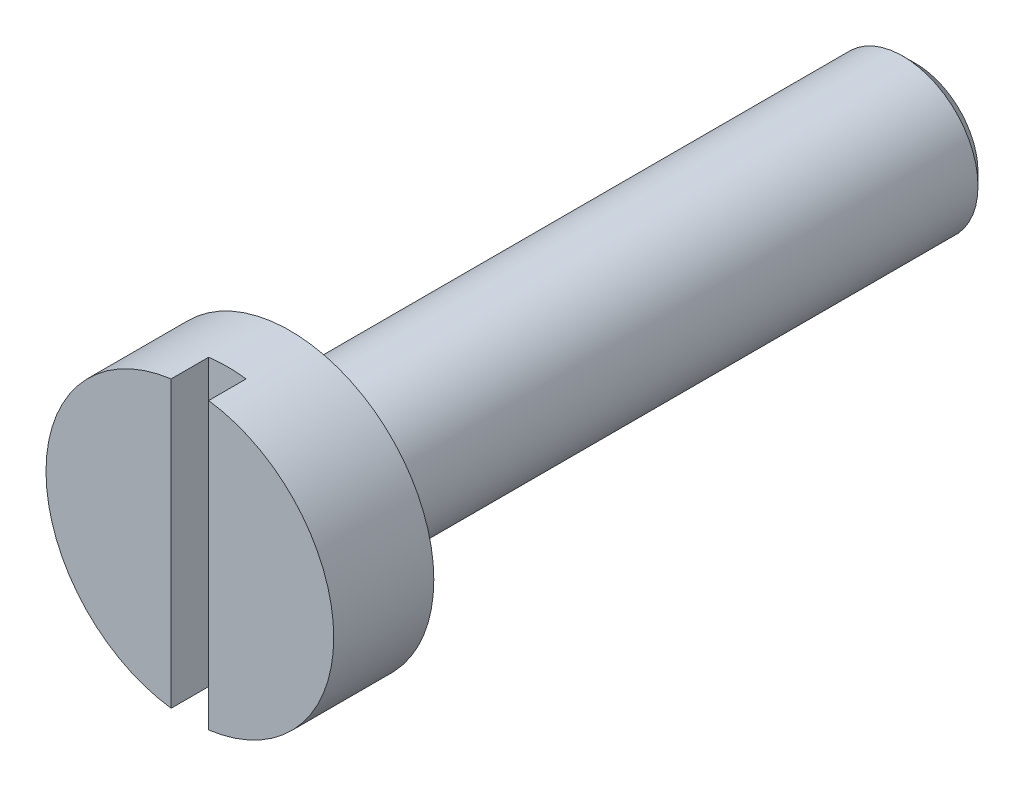
SolidWorks part; units mm, degrees
ref_plane "Спереди" through (0, 0, 0) normal (0, 0, 1) x (1, 0, 0)
ref_plane "Сверху" through (0, 0, 0) normal (0, 1, 0) x (1, 0, 0)
ref_plane "Справа" through (0, 0, 0) normal (1, 0, 0) x (0, 0, -1)
sketch "Эскиз1" plane through (0, 0, 0) normal (0, 0, 1) x (1, 0, 0)
  circle A0 centre (0, 0) radius 1.15
extrude "Бобышка-Вытянуть1" add sketch "Эскиз1" along normal blind 0.8
sketch "Эскиз2" plane through (0, 0, 0) normal (0, 0, 1) x (1, 0, 0)
  circle A0 centre (0, 0) radius 0.6
extrude "Бобышка-Вытянуть2" add sketch "Эскиз2" against normal blind 5
chamfer "Фаска1" distance 0.1 angle 45 1 edges at (0.6, 0, -5)
sketch "Эскиз3" plane through (0, 0, 0.8) normal (0, 0, 1) x (1, 0, 0)
  line L1 (0.15, -1.1946) -> (-0.15, -1.1946)
  line L2 (0.15, -1.1946) -> (0.15, 1.1946)
  line L3 (0.15, 1.1946) -> (-0.15, 1.1946)
  line L4 (-0.15, -1.1946) -> (-0.15, 1.1946)
  line L5 (0.15, -1.1946) -> (-0.15, 1.1946) construction
  line L6 (0.15, 1.1946) -> (-0.15, -1.1946) construction
  point P0 (0, 0)
extrude "Вырез-Вытянуть1" cut sketch "Эскиз3" against normal blind 0.3
